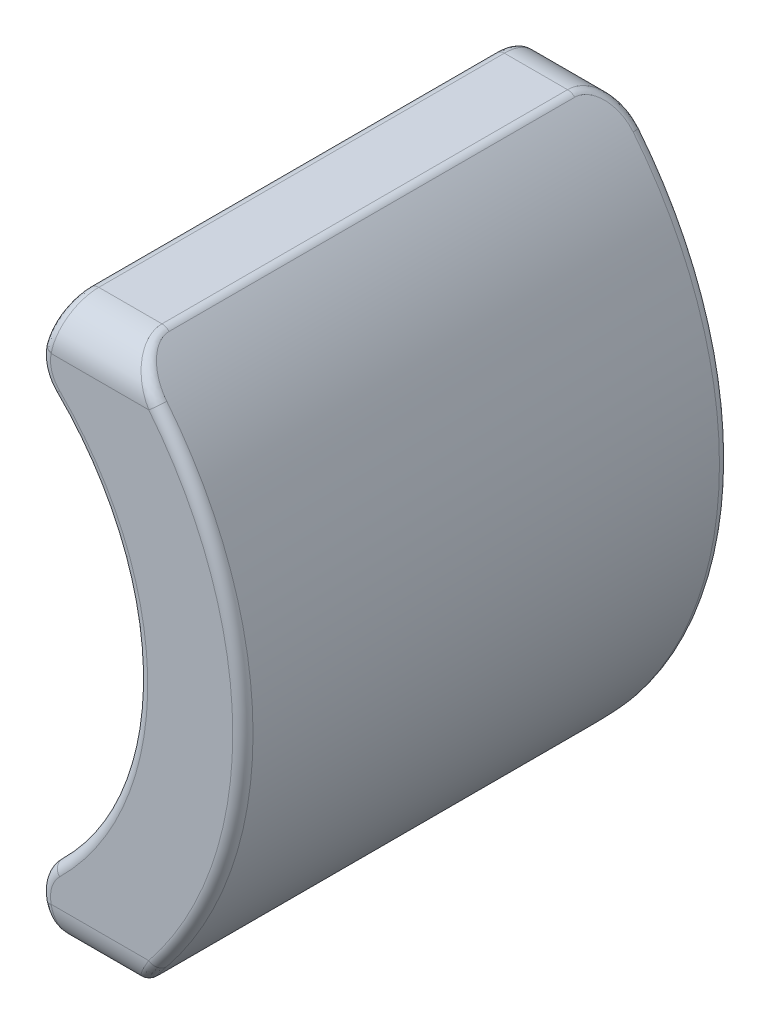
SolidWorks part; units mm, degrees
ref_plane "Front Plane" through (0, 0, 0) normal (0, 0, 1) x (1, 0, 0)
ref_plane "Top Plane" through (0, 0, 0) normal (0, 1, 0) x (1, 0, 0)
ref_plane "Right Plane" through (0, 0, 0) normal (1, 0, 0) x (0, 0, -1)
sketch "Sketch1" plane through (0, 0, 0) normal (0, 0, 1) x (1, 0, 0)
  line L0 (0, 0) -> (9.63, 0) construction
  line L1 (6.7381, -6.88) -> (4.8781, -6.88)
  line L2 (4.8781, -6.88) -> (4.5318, -5.38)
  line L3 (6.7381, 6.88) -> (4.8781, 6.88)
  line L4 (4.8781, 6.88) -> (4.5318, 5.38)
  arc A0 (6.7381, 6.88) -> (6.7381, -6.88) centre (0, 0) cw
  arc A1 (4.5318, 5.38) -> (4.5318, -5.38) centre (0, 0) cw
  dimension "D1" = 9.63
  dimension "D2" = 6.88
  dimension "D3" = 103
  dimension "D4" = 1.86
  dimension "D5" = 1.5
extrude "Boss-Extrude1" add sketch "Sketch1" along normal blind 12
fillet "Fillet1" radius 1 2 edges at (4.5318, -5.38, 6) (4.5318, 5.38, 6)
fillet "Fillet2" radius 1 4 edges at (5.8081, -6.88, 0) (5.8081, -6.88, 12) (5.8081, 6.88, 12) (5.8081, 6.88, 0)
fillet "Fillet3" radius 0.25 24 edges at (6.9882, -6.6258, 11.6661) (6.7381, -6.88, 6) (6.8685, -6.7498, 0.5066) (9.63, 0, 0) (6.9882, 6.6258, 0.3339) (6.7381, 6.88, 6) (6.8685, 6.7498, 11.4934) (4.8161, 6.6112, 11.6822) (4.8781, 6.88, 6) (4.8161, 6.6112, 0.3178) (4.6879, 5.4113, 0) (7.0343, 0, 0) (4.6879, -5.4113, 0) (4.8161, -6.6112, 0.3178) (4.8781, -6.88, 6) (4.8161, -6.6112, 11.6822) (7.0343, 0, 12) (4.6879, 5.4113, 12) (9.63, 0, 12) (4.6879, -5.4113, 12)
